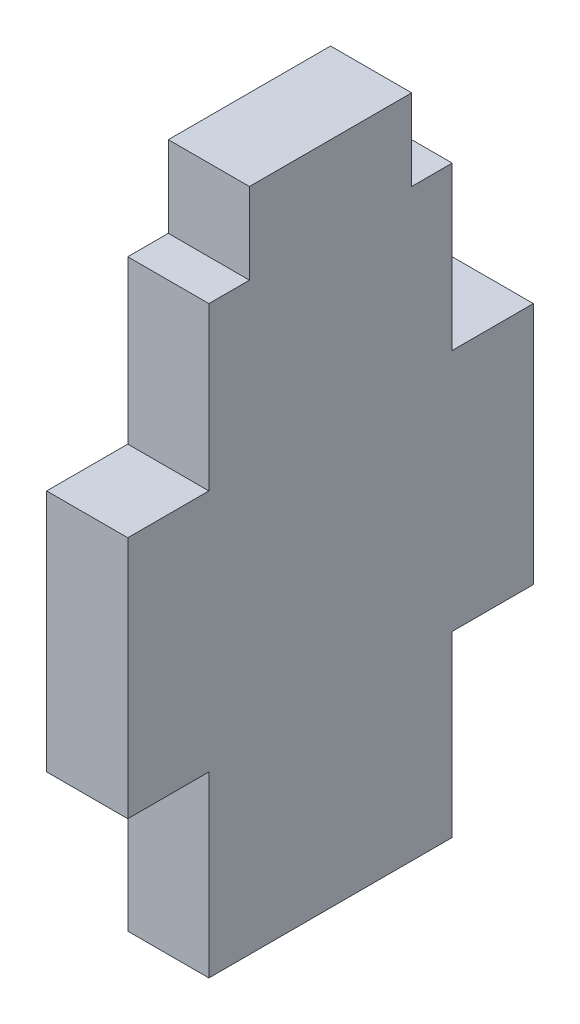
SolidWorks part; units mm, degrees
ref_plane "前视基准面" through (0, 0, 0) normal (0, 0, 1) x (1, 0, 0)
ref_plane "上视基准面" through (0, 0, 0) normal (0, 1, 0) x (1, 0, 0)
ref_plane "右视基准面" through (0, 0, 0) normal (1, 0, 0) x (0, 0, -1)
sketch "草图1" plane through (0, 0, 0) normal (1, 0, 0) x (0, 0, -1)
  line L0 (-12.5, 36) -> (-15, 36)
  line L1 (0, 0) -> (-15, 0)
  line L2 (0, 0) -> (0, 11)
  line L3 (0, 36) -> (-2.5, 36)
  line L4 (-15, 0) -> (-15, 11)
  line L6 (-12.5, 36) -> (-12.5, 41)
  line L7 (-12.5, 41) -> (-2.5, 41)
  line L8 (-2.5, 36) -> (-2.5, 41)
  line L9 (0, 26) -> (5, 26)
  line L11 (0, 11) -> (5, 11)
  line L12 (5, 26) -> (5, 11)
  line L13 (-15, 26) -> (-20, 26)
  line L15 (-15, 11) -> (-20, 11)
  line L16 (-20, 26) -> (-20, 11)
  line L17 (-15, 26) -> (-15, 36)
  line L18 (0, 26) -> (0, 36)
  dimension "D1" = 36
  dimension "D2" = 15
  dimension "D3" = 5
  dimension "D4" = 5
  dimension "D5" = 5
  dimension "D6" = 15
  dimension "D7" = 15
  dimension "D8" = 10
  dimension "D9" = 2.5
  dimension "D10" = 10
  dimension "D11" = 10
extrude "凸台-拉伸1" add sketch "草图1" along normal blind 5
